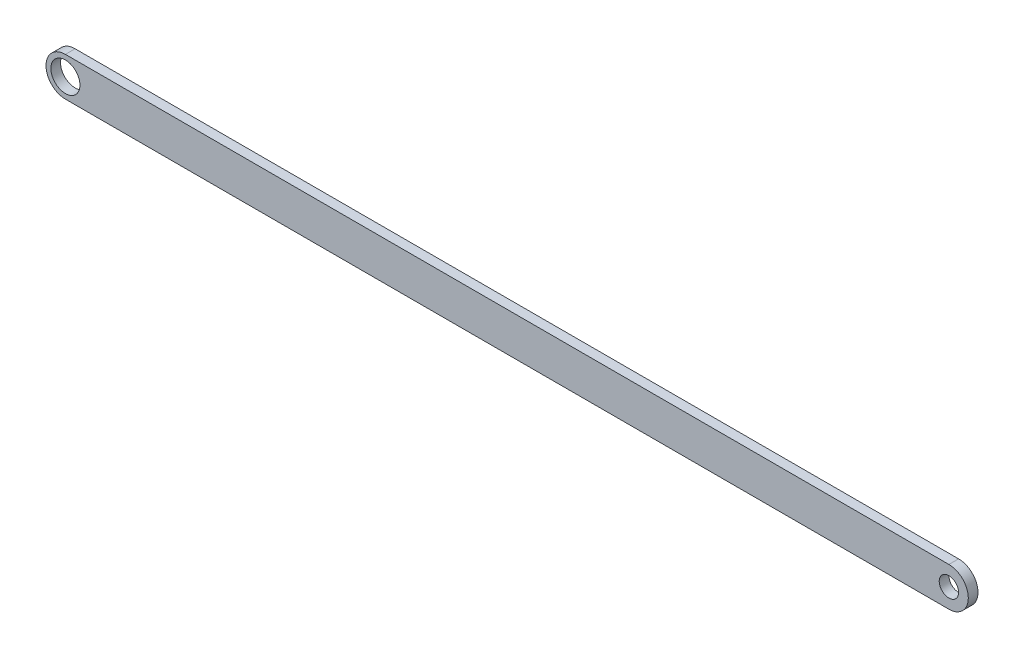
SolidWorks part; units mm, degrees
ref_plane "Plano frontal" through (0, 0, 0) normal (0, 0, 1) x (1, 0, 0)
ref_plane "Plano superior" through (0, 0, 0) normal (0, 1, 0) x (1, 0, 0)
ref_plane "Plano direito" through (0, 0, 0) normal (1, 0, 0) x (0, 0, -1)
sketch "Esboço1" plane through (0, 0, 0) normal (0, 0, 1) x (1, 0, 0)
  line L0 (-45.545, 2) -> (45.545, 2)
  line L1 (-45.545, 0) -> (45.545, 0) construction
  line L2 (-45.545, -2) -> (45.545, -2)
  arc A0 (-45.545, 2) -> (-45.545, -2) centre (-45.545, 0) ccw
  arc A1 (45.545, 2) -> (45.545, -2) centre (45.545, 0) cw
  circle A2 centre (-45.545, 0) radius 1.5
  circle A3 centre (45.545, 0) radius 1
  point P3 (0, 2)
  dimension "D3" = 3
  dimension "D1" = 91.09
  dimension "D2" = 2
extrude "Ressalto-extrusão1" add sketch "Esboço1" along normal blind 1
